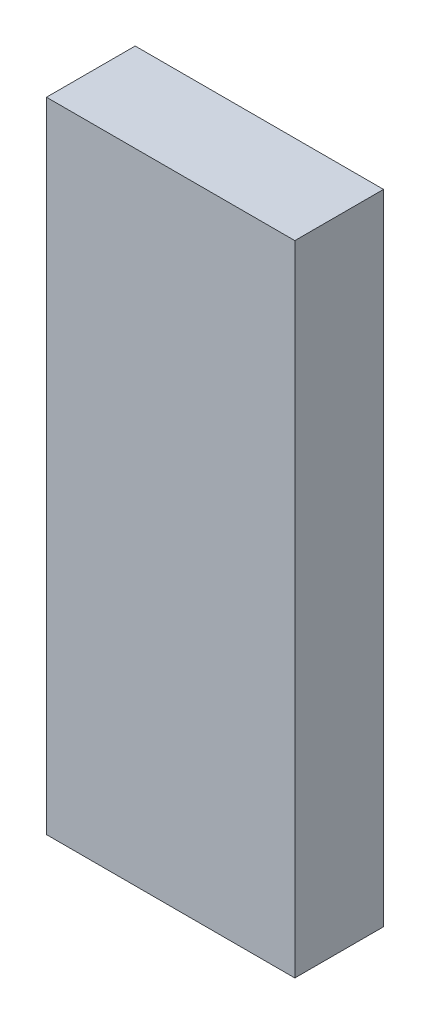
SolidWorks part; units mm, degrees
ref_plane "Front Plane" through (0, 0, 0) normal (0, 0, 1) x (1, 0, 0)
ref_plane "Top Plane" through (0, 0, 0) normal (0, 1, 0) x (1, 0, 0)
ref_plane "Right Plane" through (0, 0, 0) normal (1, 0, 0) x (0, 0, -1)
sketch "Sketch1" plane through (0, 0, 0) normal (0, 0, 1) x (1, 0, 0)
  line L0 (3650, 500) -> (3650, 680)
  line L1 (3650, 680) -> (3720, 680)
  line L2 (3720, 680) -> (3720, 500)
  line L3 (3720, 500) -> (3650, 500)
extrude "Boss-Extrude1" add sketch "Sketch1" along normal blind 25
